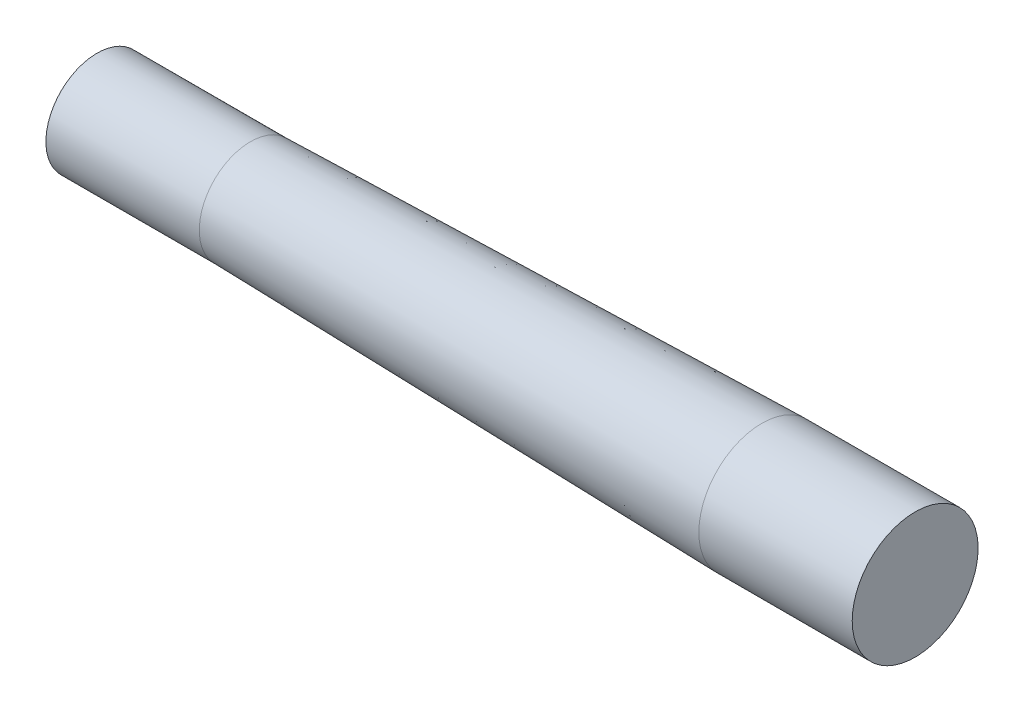
SolidWorks part; units mm, degrees
ref_plane "Front Plane" through (0, 0, 0) normal (0, 0, 1) x (1, 0, 0)
ref_plane "Top Plane" through (0, 0, 0) normal (0, 1, 0) x (1, 0, 0)
ref_plane "Right Plane" through (0, 0, 0) normal (1, 0, 0) x (0, 0, -1)
sketch "Sketch1" plane through (0, 0, 0) normal (0, 0, 1) x (1, 0, 0)
  line L0 (0, 0) -> (4.4154, -89.4596) construction
  line L1 (0, 102.108) -> (1021.3732, 152.5187)
  line L3 (0, 0) -> (79.8822, 3.9426) construction
  dimension "D1" = 90
sketch "Sketch7" plane through (0, 0, 0) normal (1, 0, 0) x (0, 0, -1)
  circle A0 centre (0, 0) radius 102.108
ref_plane "Plane2" through (1021.3732, 0, 0) normal (1, 0, 0) x (0, 0, -1)
sketch "Sketch8" plane through (0, 0, 0) normal (0, 0, 1) x (1, 0, 0)
  line L0 (0, 0) -> (1016.5569, 0)
ref_plane "Plane3" through (1021.3732, 0, 0) normal (1, 0, 0) x (0, 0, -1)
sketch "Sketch9" plane through (1021.3732, 0, 0) normal (1, 0, 0) x (0, 0, -1)
  circle A0 centre (0, 0) radius 125.73
  dimension "D1" = 251.46
loft "Loft3" add profiles "Sketch7", "Sketch9"
sketch "Sketch11" plane through (0, 0, 0) normal (-1, 0, 0) x (0, 0, 1)
  circle A0 centre (0, 0) radius 102.108
extrude "Boss-Extrude1" add sketch "Sketch11" along normal blind 306.324
sketch "Sketch12" plane through (1021.3732, 0, 0) normal (1, 0, 0) x (0, 0, -1)
  circle A0 centre (0, 0) radius 125.73
  circle A1 centre (0, 0) radius 125.73
extrude "Boss-Extrude2" add sketch "Sketch12" along normal blind 306.324 contours A0
